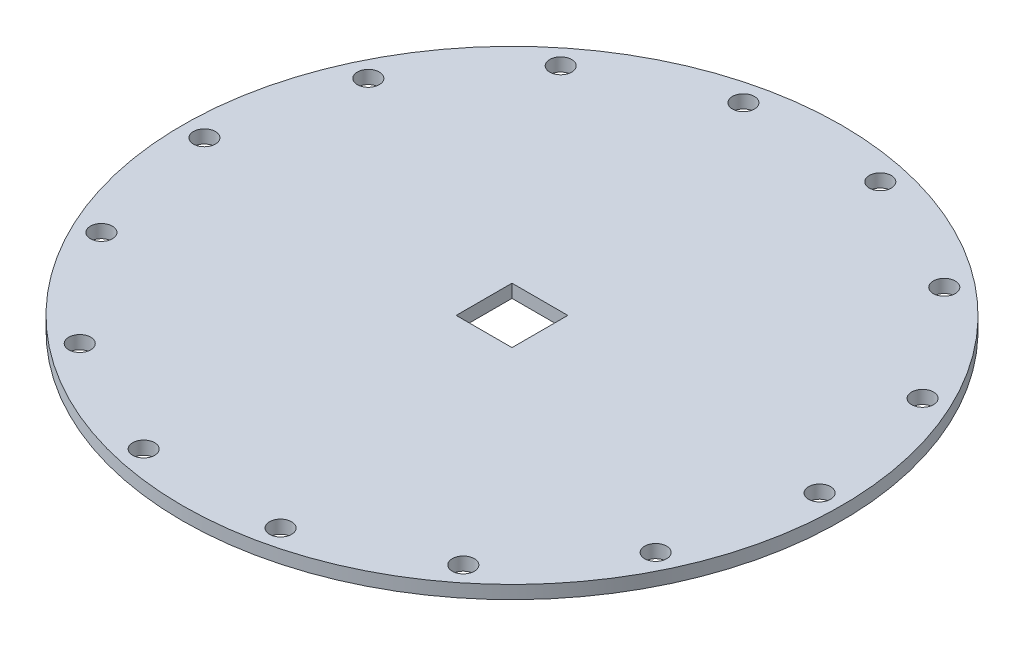
SolidWorks part; units mm, degrees
ref_plane "Alzado" through (0, 0, 0) normal (0, 0, 1) x (1, 0, 0)
ref_plane "Planta" through (0, 0, 0) normal (0, 1, 0) x (1, 0, 0)
ref_plane "Vista lateral" through (0, 0, 0) normal (1, 0, 0) x (0, 0, -1)
sketch "Croquis1" plane through (0, 0, 0) normal (0, 1, 0) x (1, 0, 0)
  circle A0 centre (0, 0) radius 150
  dimension "D1" = 300
extrude "Saliente-Extruir1" add sketch "Croquis1" along normal blind 6
sketch "Croquis2" plane through (0, 0, 0) normal (0, -1, 0) x (1, 0, 0)
  line L0 (0, 0) -> (140, 0) construction
  line L1 (0, 0) -> (126.1356, -60.7437) construction
  circle A0 centre (140, 0) radius 5
  circle A1 centre (126.1356, -60.7437) radius 5
  circle A2 centre (87.2886, -109.4564) radius 5
  circle A3 centre (31.1529, -136.4899) radius 5
  circle A4 centre (-31.1529, -136.4899) radius 5
  circle A5 centre (-87.2886, -109.4564) radius 5
  circle A6 centre (-126.1356, -60.7437) radius 5
  circle A7 centre (-140, 0) radius 5
  circle A8 centre (-126.1356, 60.7437) radius 5
  circle A9 centre (-87.2886, 109.4564) radius 5
  circle A10 centre (-31.1529, 136.4899) radius 5
  circle A11 centre (31.1529, 136.4899) radius 5
  circle A12 centre (87.2886, 109.4564) radius 5
  circle A13 centre (126.1356, 60.7437) radius 5
  dimension "D2" = 10
  dimension "D1" = 140
  dimension "D4" = 25.714
  dimension "D3" = 14
extrude "Cortar-Extruir1" cut sketch "Croquis2" against normal through all
sketch "Croquis4" plane through (0, 0, 0) normal (0, -1, 0) x (1, 0, 0)
  line L1 (-12.7, -12.7) -> (12.7, -12.7)
  line L2 (-12.7, -12.7) -> (-12.7, 12.7)
  line L3 (-12.7, 12.7) -> (12.7, 12.7)
  line L4 (12.7, -12.7) -> (12.7, 12.7)
  line L5 (-12.7, -12.7) -> (12.7, 12.7) construction
  line L6 (-12.7, 12.7) -> (12.7, -12.7) construction
  point P0 (0, 0)
  dimension "D1" = 25.4
extrude "Cortar-Extruir2" cut sketch "Croquis4" against normal through all
